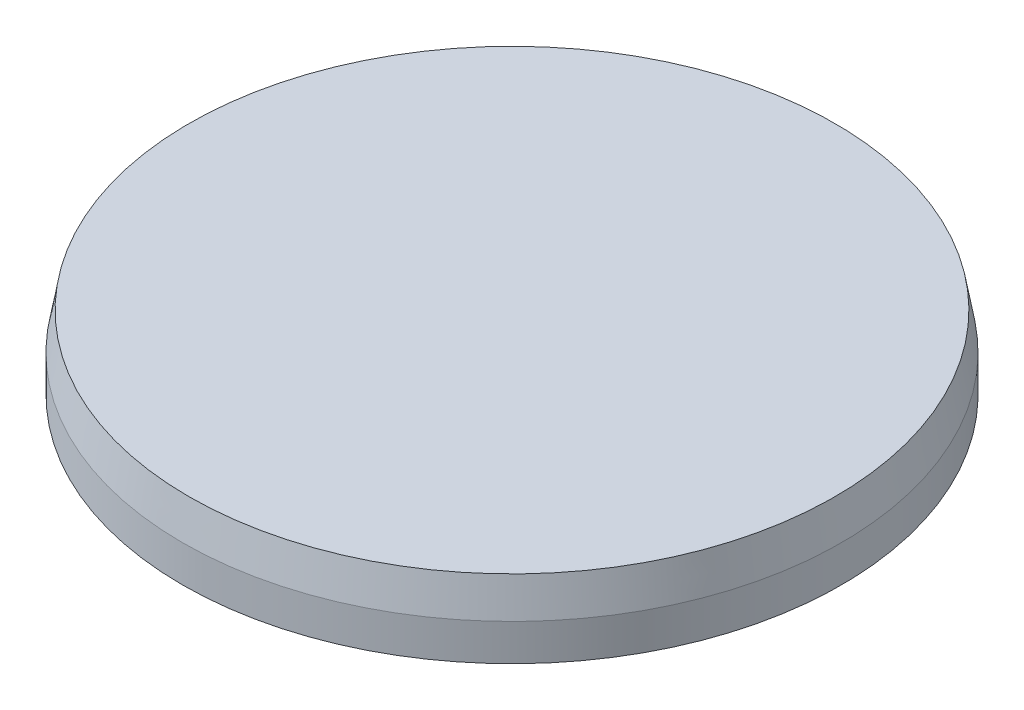
SolidWorks part; units mm, degrees
ref_plane "前视基准面" through (0, 0, 0) normal (0, 0, 1) x (1, 0, 0)
ref_plane "上视基准面" through (0, 0, 0) normal (0, 1, 0) x (1, 0, 0)
ref_plane "右视基准面" through (0, 0, 0) normal (1, 0, 0) x (0, 0, -1)
sketch "草图1" plane through (0, 0, 0) normal (0, 1, 0) x (1, 0, 0)
  circle A0 centre (0, 0) radius 9
  dimension "D1" = 18
extrude "凸台-拉伸1" add sketch "草图1" along normal blind 2
chamfer "倒角1" distance 1 angle 10 1 edges at (0, 2, 9)
